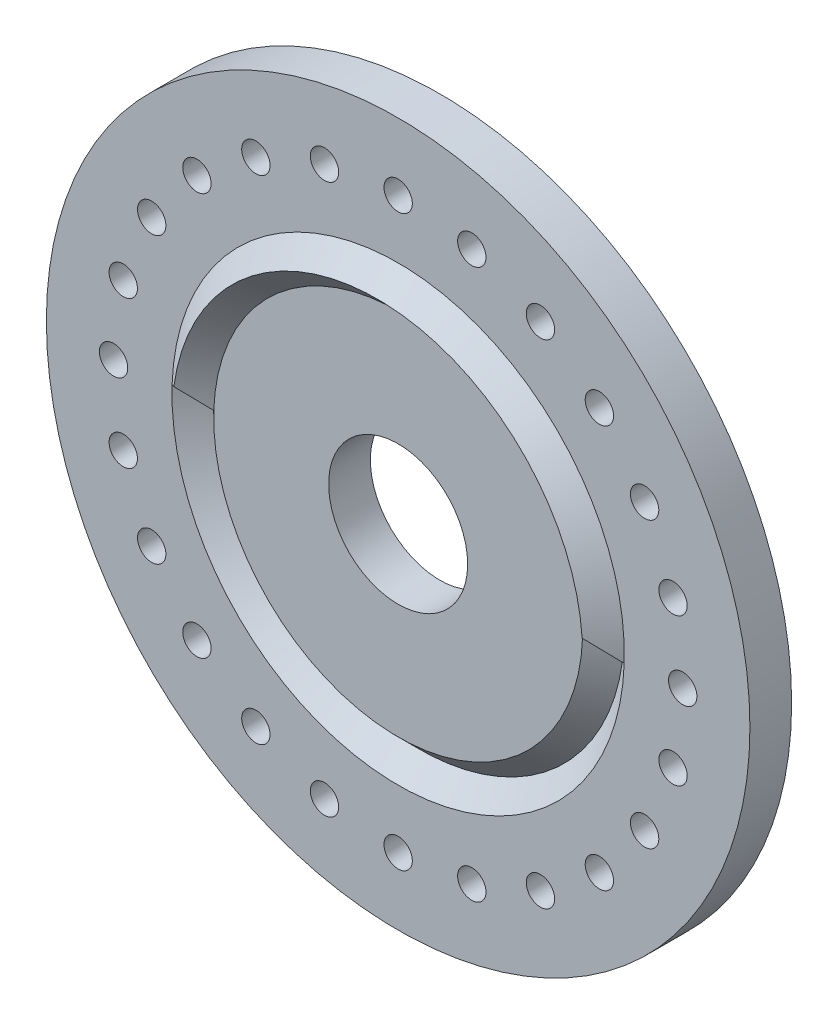
SolidWorks part; units mm, degrees
ref_plane "Front Plane" through (0, 0, 0) normal (0, 0, 1) x (1, 0, 0)
ref_plane "Top Plane" through (0, 0, 0) normal (0, 1, 0) x (1, 0, 0)
ref_plane "Right Plane" through (0, 0, 0) normal (1, 0, 0) x (0, 0, -1)
sketch "Sketch1" plane through (0, 0, 0) normal (0, 0, 1) x (1, 0, 0)
  circle A0 centre (0, 0) radius 64.2685
  point P3 (0, 0)
  dimension "D1" = 128.537
extrude "Boss-Extrude1" add sketch "Sketch1" along normal blind 7.62
hole_wizard "#6 (0.204) Diameter Hole1" positions "Sketch2" profile "Sketch3" hole size "#6" standard "ANSI Inch" end condition through all
sketch "Sketch2" plane through (0, 0, 0) normal (0, 0, 1) x (1, 0, 0)
  point P0 (-51.9902, 0)
sketch "Sketch3" plane through (-51.9902, 0, 0) normal (1, 0, 0) x (0, 1, 0)
  line L0 (0, 0) -> (0, 7.62)
  line L1 (0, 7.62) -> (2.5908, 7.62)
  line L2 (2.5908, 7.62) -> (2.5908, 0)
  line L5 (2.5908, 0) -> (0, 0)
  line L11 (0, -6.35) -> (0, 107.95) construction
  dimension "Thru Hole Dia." = 5.1816
  dimension "Thru Hole Depth" = 7.62
pattern_circular "CirPattern2" count 24 over 360 about axis through (0, 0, 0) along (0, 0, 1) of "#6 (0.204) Diameter Hole1"
sketch "Sketch5" plane through (0, 0, 0) normal (0, 0, 1) x (1, 0, 0)
  circle A0 centre (0, 0) radius 12.7
extrude "Cut-Extrude1" cut sketch "Sketch5" along normal blind 10.16 and the other way blind 2.54 contours A0
ref_plane "Plane1" through (0, 0, -2.54) normal (0, 0, -1) x (-1, 0, 0)
sketch "Sketch38" plane through (0, 0, 7.62) normal (0, 0, 1) x (1, 0, 0)
  arc A0 (33.6849, -1.1301) -> (-33.6849, 1.1301) centre (0, 0) ccw
extrude "Extrude-Thin3" add sketch "Sketch38" along normal blind 5.08 draft 45 thin
sketch "Sketch48" plane through (0, 0, 7.62) normal (0, 0, 1) x (1, 0, 0)
  line L0 (41.3006, -1.3856) -> (33.6849, -1.1301) construction
  line L1 (-33.6849, 1.1301) -> (-41.3006, 1.3856) construction
  arc A0 (41.3006, -1.3856) -> (-41.3006, 1.3856) centre (0, 0) cw
extrude "Cut-Extrude-Thin1" cut sketch "Sketch48" against normal blind 5.08 draft 45 thin contours A0
